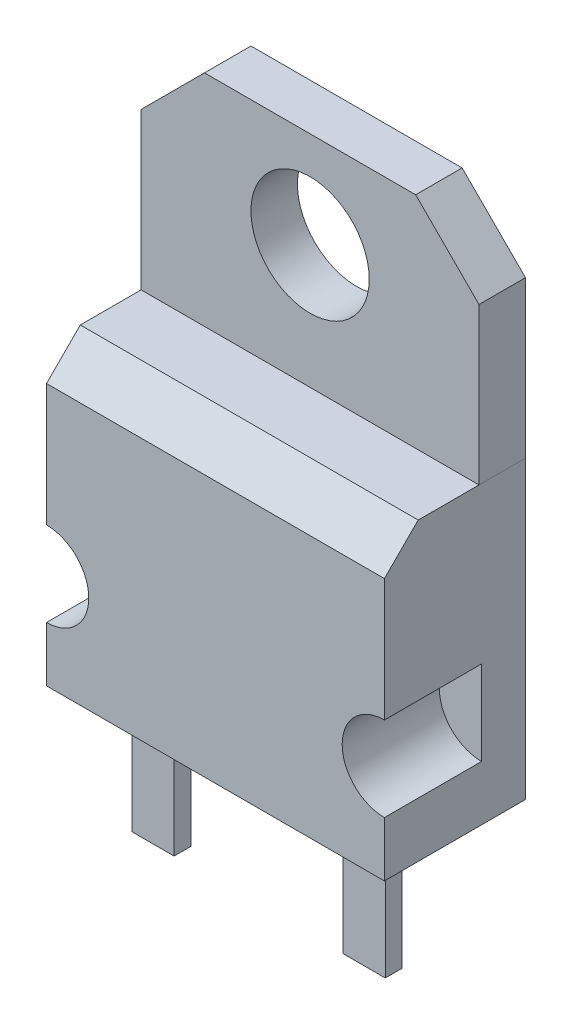
SolidWorks part; units mm, degrees
ref_plane "Front" through (0, 0, 0) normal (0, 0, 1) x (1, 0, 0)
ref_plane "Top" through (0, 0, 0) normal (0, 1, 0) x (1, 0, 0)
ref_plane "Right" through (0, 0, 0) normal (1, 0, 0) x (0, 0, -1)
sketch "Sketch2" plane through (0, 0, 0) normal (0, 0, 1) x (1, 0, 0)
  line L1 (-5.08, 3.302) -> (5.08, 3.302)
  line L2 (-5.08, 3.302) -> (-5.08, -3.302)
  line L3 (-5.08, -3.302) -> (5.08, -3.302)
  line L4 (5.08, 3.302) -> (5.08, -3.302)
  line L5 (-5.08, 3.302) -> (5.08, -3.302) construction
  line L6 (-5.08, -3.302) -> (5.08, 3.302) construction
  line L7 (-3.81, -3.302) -> (3.81, -3.302)
  line L8 (-3.81, -3.302) -> (-3.81, -9.144)
  line L9 (-3.81, -9.144) -> (3.81, -9.144)
  line L10 (3.81, -3.302) -> (3.81, -9.144)
  point P0 (0, 0)
  dimension "D1" = 6.604
  dimension "D2" = 10.16
  dimension "D3" = 5.842
  dimension "D4" = 7.62
  dimension "D5" = 1.27
extrude "Boss-Extrude1" add sketch "Sketch2" along normal blind 1.397 contours L4 L1 L2 L3 | L10 L3 L8 L9
sketch "Sketch3" plane through (0, 0, 1.397) normal (0, 0, 1) x (1, 0, 0)
  line L0 (5.08, 3.302) -> (5.08, -3.302) construction
  line L1 (-5.08, 3.302) -> (5.08, 3.302) construction
  circle A0 centre (0, 0.4064) radius 1.778
  dimension "D1" = 3.556
  dimension "D2" = 5.08
  dimension "D3" = 2.8956
extrude "Cut-Extrude1" cut sketch "Sketch3" against normal through all
sketch "Sketch4" plane through (0, 0, 0) normal (0, 0, 1) x (1, 0, 0)
  line L1 (-5.08, -3.302) -> (5.08, -3.302)
  line L2 (-5.08, -3.302) -> (-5.08, -12.192)
  line L3 (-5.08, -12.192) -> (5.08, -12.192)
  line L4 (5.08, -3.302) -> (5.08, -12.192)
  line L5 (-5.08, -3.302) -> (5.08, -12.192) construction
  line L6 (-5.08, -12.192) -> (5.08, -3.302) construction
  line L7 (3.81, -3.302) -> (5.08, -3.302) construction
  line L8 (3.81, -3.302) -> (3.81, -9.144) construction
  point P0 (0, -7.747)
  dimension "D1" = 10.16
  dimension "D2" = 8.89
  dimension "D3" = 1.27
extrude "Boss-Extrude2" add sketch "Sketch4" along normal blind 4.2418 separate body
sketch "Sketch7" plane through (0, 0, 0) normal (0, 0, -1) x (-1, 0, 0)
  line L0 (-5.08, -3.302) -> (5.08, -3.302) construction
  line L1 (-3.81, -3.302) -> (3.81, -3.302)
  line L2 (-3.81, -3.302) -> (-3.81, -9.144)
  line L3 (-3.81, -9.144) -> (3.81, -9.144)
  line L4 (3.81, -3.302) -> (3.81, -9.144)
  line L5 (-5.08, -12.192) -> (-5.08, -3.302) construction
  dimension "D1" = 5.842
  dimension "D2" = 7.62
  dimension "D3" = 1.27
extrude "Cut-Extrude3" cut sketch "Sketch7" against normal blind 1.397
sketch "Sketch8" plane through (0, -12.192, 0) normal (0, -1, 0) x (1, 0, 0)
  line L0 (-5.08, 0) -> (5.08, 0) construction
  line L1 (-3.81, 2.9464) -> (-2.54, 2.9464)
  line L2 (-3.81, 2.9464) -> (-3.81, 2.4384)
  line L3 (-3.81, 2.4384) -> (-2.54, 2.4384)
  line L4 (-2.54, 2.9464) -> (-2.54, 2.4384)
  line L5 (-3.81, 2.9464) -> (-2.54, 2.4384) construction
  line L6 (-3.81, 2.4384) -> (-2.54, 2.9464) construction
  line L7 (2.54, 2.9464) -> (3.81, 2.9464)
  line L8 (2.54, 2.9464) -> (2.54, 2.4384)
  line L9 (2.54, 2.4384) -> (3.81, 2.4384)
  line L10 (3.81, 2.9464) -> (3.81, 2.4384)
  line L11 (2.54, 2.9464) -> (3.81, 2.4384) construction
  line L12 (2.54, 2.4384) -> (3.81, 2.9464) construction
  line L13 (-5.08, 4.2418) -> (-5.08, 0) construction
  line L20 (5.08, 4.2418) -> (5.08, 0) construction
  point P0 (-3.175, 2.6924)
  point P5 (3.175, 2.6924)
  dimension "D1" = 2.4384
  dimension "D2" = 2.4384
  dimension "D3" = 0.508
  dimension "D4" = 0.508
  dimension "D6" = 1.27
  dimension "D7" = 1.27
  dimension "D9" = 1.27
  dimension "D10" = 1.27
extrude "Boss-Extrude3" add sketch "Sketch8" along normal blind 3.81 separate body
chamfer "Chamfer1" distance 1.905 angle 45 2 edges at (-5.08, 3.302, 0.6985) (5.08, 3.302, 0.6985)
chamfer "Chamfer2" distance 1.016 angle 45 1 edges at (0, -3.302, 4.2418)
sketch "Sketch10" plane through (0, 0, 4.2418) normal (0, 0, 1) x (1, 0, 0)
  line L0 (5.08, -12.192) -> (5.08, -4.318) construction
  line L1 (-5.08, -4.318) -> (-5.08, -12.192) construction
  line L2 (-5.08, -12.192) -> (5.08, -12.192) construction
  circle A0 centre (5.08, -9.271) radius 1.27
  circle A1 centre (-5.08, -9.271) radius 1.27
  dimension "D2" = 2.54
  dimension "D3" = 2.54
  dimension "D1" = 2.921
extrude "Cut-Extrude4" cut sketch "Sketch10" against normal blind 2.921
